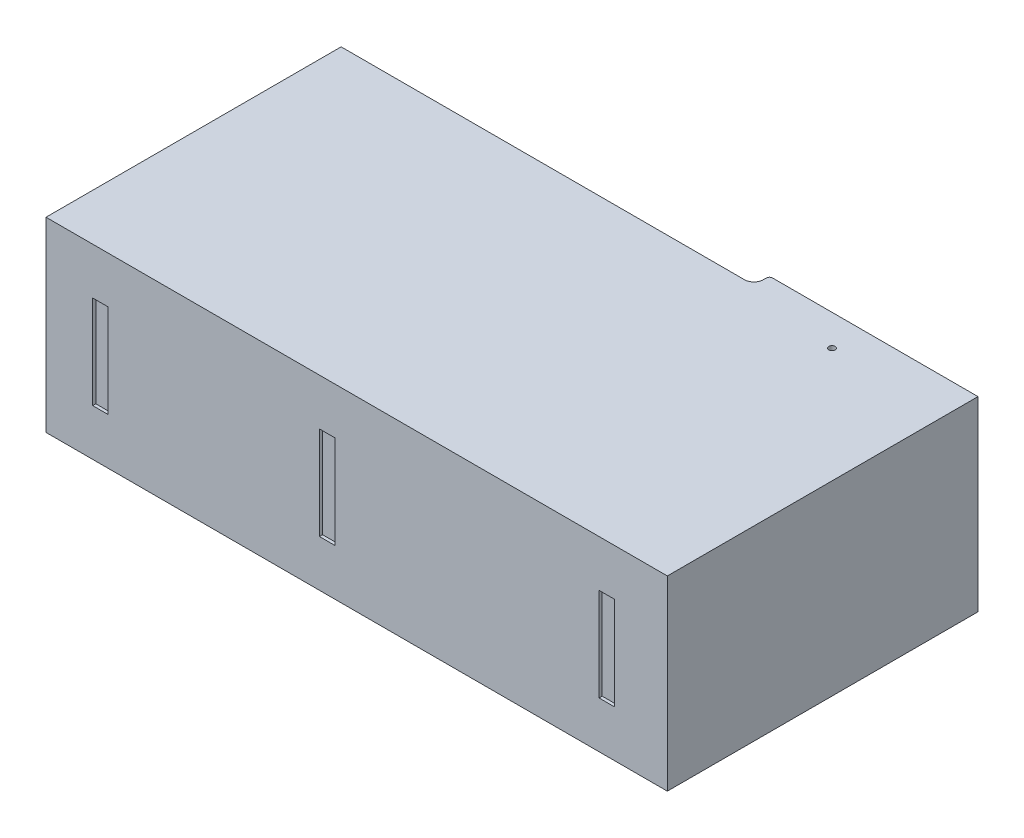
SolidWorks part; units mm, degrees
material "Plástico personalizado"
ref_plane "Alzado" through (0, 0, 0) normal (0, 0, 1) x (1, 0, 0)
ref_plane "Planta" through (0, 0, 0) normal (0, 1, 0) x (1, 0, 0)
ref_plane "Vista lateral" through (0, 0, 0) normal (1, 0, 0) x (0, 0, -1)
sketch "Croquis1" plane through (0, 0, 0) normal (0, 1, 0) x (1, 0, 0)
  line L0 (-10, 4.5) -> (-10, 5)
  line L1 (10, -5) -> (-10, -5)
  line L2 (10, -5) -> (10, 5)
  line L3 (10, 5) -> (-10, 5)
  line L4 (-10, -5) -> (-10, 5)
  line L5 (10, -5) -> (-10, 5) construction
  line L6 (10, 5) -> (-10, -5) construction
  line L7 (-10, 4.5) -> (2.9867, 4.5)
  line L8 (3.2867, 4.8) -> (3.2867, 5)
  line L9 (3.2867, 5) -> (10, 5)
  arc A0 (3.2867, 4.8) -> (2.9867, 4.5) centre (2.9867, 4.8) cw
  point P0 (0, 0)
  dimension "D4" = 0.3
  dimension "D1" = 10
  dimension "D2" = 20
  dimension "D3" = 0.5
extrude "Saliente-Extruir2" add sketch "Croquis1" along normal blind 6 contours L8 A0 L7 L4 L1 L2 L3
fillet "Redondeo1" radius 0.1 1 edges at (3.2867, 3, -5)
sketch "Croquis3" plane through (0, 0, -4.5) normal (0, 0, -1) x (-1, 0, 0)
  line L0 (-3.3867, 0) -> (-3.3867, 6) construction
  line L1 (0.6133, 1.35) -> (-1.3867, 1.35)
  line L2 (0.6133, 1.35) -> (0.6133, 4.65)
  line L3 (0.6133, 4.65) -> (-1.3867, 4.65)
  line L4 (-1.3867, 1.35) -> (-1.3867, 4.65)
  line L5 (0.6133, 1.35) -> (-1.3867, 4.65) construction
  line L6 (0.6133, 4.65) -> (-1.3867, 1.35) construction
  line L8 (10, 0) -> (-2.9867, 0) construction
  point P0 (-0.3867, 3)
  dimension "D1" = 2
  dimension "D2" = 2
  dimension "D3" = 3.3
  dimension "D4" = 3
extrude "Cortar-Extruir2" cut sketch "Croquis3" against normal blind 5
sketch "Croquis4" plane through (0, 6, 0) normal (0, 1, 0) x (1, 0, 0)
  line L0 (10, 4) -> (6.3, 4)
  line L1 (10, -5) -> (10, 5) construction
  line L2 (10, 5) -> (10, 4)
  circle A0 centre (6.3, 4) radius 0.1
  dimension "D3" = 0.2
  dimension "D1" = 3.7
  dimension "D2" = 1
extrude "Cortar-Extruir3" cut sketch "Croquis4" against normal up to surface (6 mm away) up to face at (1.6235, 0, -2.3323)
sketch "Croquis5" plane through (0, 0, 5) normal (0, 0, 1) x (1, 0, 0)
  line L0 (-10, 3) -> (10, 3) construction
  line L1 (-10, 6) -> (-10, 0) construction
  line L2 (10, 6) -> (10, 0) construction
  line L4 (-7.9972, 1.5) -> (-8.4972, 1.5)
  line L5 (-7.9972, 1.5) -> (-7.9972, 4.5)
  line L6 (-7.9972, 4.5) -> (-8.4972, 4.5)
  line L7 (-8.4972, 1.5) -> (-8.4972, 4.5)
  line L8 (-7.9972, 1.5) -> (-8.4972, 4.5) construction
  line L9 (-7.9972, 4.5) -> (-8.4972, 1.5) construction
  line L10 (-0.6972, 1.5) -> (-1.1972, 1.5)
  line L11 (-0.6972, 1.5) -> (-0.6972, 4.5)
  line L12 (-0.6972, 4.5) -> (-1.1972, 4.5)
  line L13 (-1.1972, 1.5) -> (-1.1972, 4.5)
  line L14 (-0.6972, 1.5) -> (-1.1972, 4.5) construction
  line L15 (-0.6972, 4.5) -> (-1.1972, 1.5) construction
  line L16 (8.3028, 1.5) -> (7.8028, 1.5)
  line L17 (8.3028, 1.5) -> (8.3028, 4.5)
  line L18 (8.3028, 4.5) -> (7.8028, 4.5)
  line L19 (7.8028, 1.5) -> (7.8028, 4.5)
  line L20 (8.3028, 1.5) -> (7.8028, 4.5) construction
  line L21 (8.3028, 4.5) -> (7.8028, 1.5) construction
  point P6 (-8.2472, 3)
  point P11 (-0.9472, 3)
  point P16 (8.0528, 3)
  dimension "D1" = 0.5
  dimension "D2" = 0.5
  dimension "D3" = 0.5
  dimension "D4" = 3
  dimension "D5" = 3
  dimension "D6" = 3
  dimension "D7" = 7.8
  dimension "D8" = 9.5
extrude "Cortar-Extruir4" cut sketch "Croquis5" against normal blind 0.1
